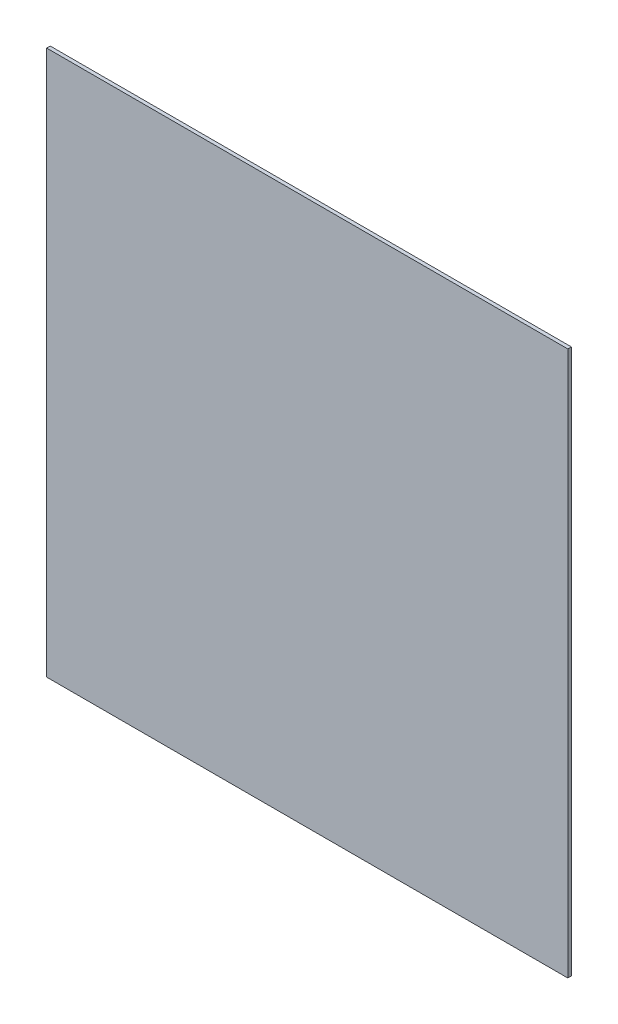
SolidWorks part; units mm, degrees
ref_plane "Front Plane" through (0, 0, 0) normal (0, 0, 1) x (1, 0, 0)
ref_plane "Top Plane" through (0, 0, 0) normal (0, 1, 0) x (1, 0, 0)
ref_plane "Right Plane" through (0, 0, 0) normal (1, 0, 0) x (0, 0, -1)
sketch "Sketch1" plane through (0, 0, 0) normal (0, 0, 1) x (1, 0, 0)
  line L0 (0, 427.6735) -> (0, 0) construction
  line L1 (0, 0) -> (427.6735, 0) construction
  line L3 (-220, 230) -> (220, 230)
  line L4 (-220, 230) -> (-220, -230)
  line L5 (-220, -230) -> (220, -230)
  line L6 (220, 230) -> (220, -230)
  dimension "D1" = 460
  dimension "D2" = 440
extrude "Boss-Extrude1" add sketch "Sketch1" along normal blind 3
